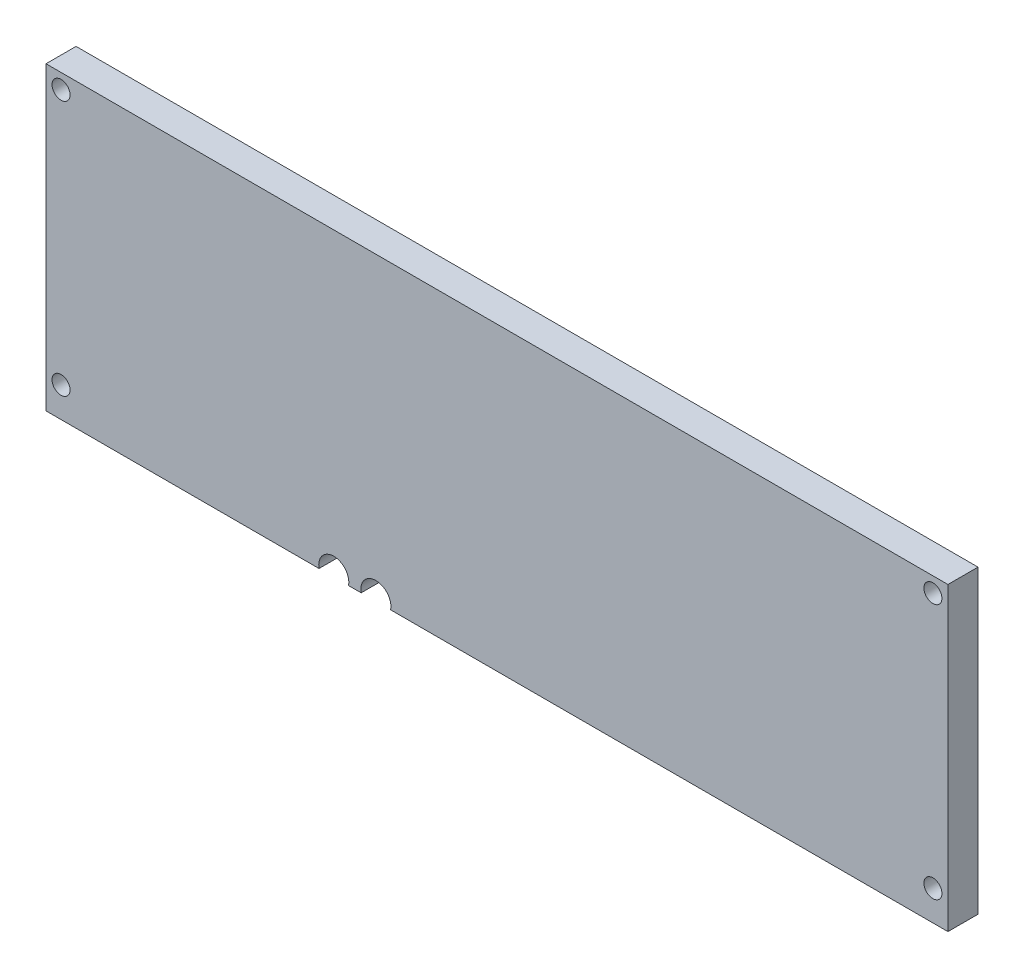
SolidWorks part; units mm, degrees
ref_plane "Front Plane" through (0, 0, 0) normal (0, 0, 1) x (1, 0, 0)
ref_plane "Top Plane" through (0, 0, 0) normal (0, 1, 0) x (1, 0, 0)
ref_plane "Right Plane" through (0, 0, 0) normal (1, 0, 0) x (0, 0, -1)
sketch "Sketch1" plane through (0, 0, 0) normal (0, 0, 1) x (1, 0, 0)
  line L1 (0, 0) -> (150, 0)
  line L2 (0, 0) -> (0, 50)
  line L3 (0, 50) -> (150, 50)
  line L4 (150, 0) -> (150, 50)
  dimension "D1" = 50
  dimension "D2" = 150
extrude "Boss-Extrude1" add sketch "Sketch1" along normal blind 5
sketch "Sketch2" plane through (0, 0, 5) normal (0, 0, 1) x (1, 0, 0)
  line L0 (0, 50) -> (0, 0) construction
  line L1 (0, 0) -> (150, 0) construction
  line L2 (150, 50) -> (0, 50) construction
  line L3 (150, 0) -> (150, 50) construction
  circle A0 centre (2.5, 5) radius 1.5
  circle A1 centre (2.5, 47.5) radius 1.5
  circle A2 centre (147.5, 47.5) radius 1.5
  circle A3 centre (147.5, 5) radius 1.5
  dimension "D1" = 2.5
  dimension "D2" = 5
  dimension "D3" = 2.5
  dimension "D4" = 2.5
  dimension "D5" = 3
  dimension "D6" = 2.5
  dimension "D7" = 2.5
  dimension "D8" = 3
  dimension "D9" = 2.5
  dimension "D10" = 5
  dimension "D11" = 3
  dimension "D12" = 3
extrude "Cut-Extrude1" cut sketch "Sketch2" against normal blind 10
sketch "Sketch3" plane through (0, 0, 0) normal (0, 0, -1) x (-1, 0, 0)
  line L0 (0, 0) -> (-150, 0) construction
  circle A0 centre (-54.8606, 0.5) radius 2.5
  circle A1 centre (-47.8577, 0.5) radius 2.5
  dimension "D3" = 5
  dimension "D4" = 5
  dimension "D1" = 0.5
  dimension "D2" = 0.5
extrude "Cut-Extrude2" cut sketch "Sketch3" against normal through all
